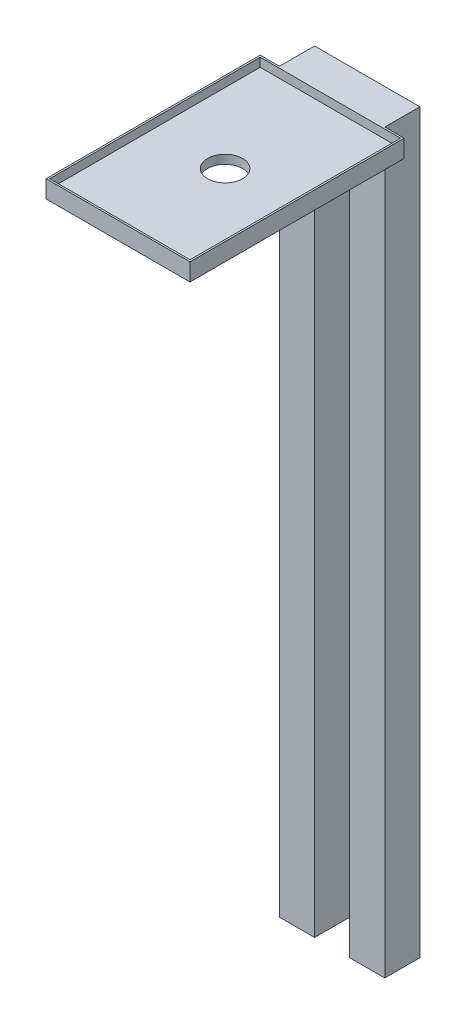
SolidWorks part; units mm, degrees
ref_plane "Front Plane" through (0, 0, 0) normal (0, 0, 1) x (1, 0, 0)
ref_plane "Top Plane" through (0, 0, 0) normal (0, 1, 0) x (1, 0, 0)
ref_plane "Right Plane" through (0, 0, 0) normal (1, 0, 0) x (0, 0, -1)
sketch "Sketch1" plane through (0, 0, 0) normal (0, 1, 0) x (1, 0, 0)
  line L1 (-20, 30) -> (20, 30)
  line L2 (-20, 30) -> (-20, -30)
  line L3 (-20, -30) -> (20, -30)
  line L4 (20, 30) -> (20, -30)
  line L5 (-20, 30) -> (20, -30) construction
  line L6 (-20, -30) -> (20, 30) construction
  circle A0 centre (0, 0) radius 5
  point P0 (0, 0)
  dimension "D1" = 10
  dimension "D2" = 60
  dimension "D3" = 40
extrude "Boss-Extrude1" add sketch "Sketch1" along normal blind 2.5
sketch "Sketch2" plane through (0, 0, 0) normal (0, -1, 0) x (1, 0, 0)
  line L0 (20.5, -30.5) -> (20.5, 30.5)
  line L1 (20.5, 30.5) -> (-20.5, 30.5)
  line L2 (-20.5, 30.5) -> (-20.5, -30.5)
  line L3 (-20.5, -30.5) -> (20.5, -30.5)
  line L4 (20, -30) -> (20, 30)
  line L5 (20, 30) -> (-20, 30)
  line L6 (-20, 30) -> (-20, -30)
  line L7 (-20, -30) -> (20, -30)
  line L8 (20, -30) -> (20, 30)
  line L9 (20, 30) -> (-20, 30)
  line L10 (-20, 30) -> (-20, -30)
  line L11 (-20, -30) -> (20, -30)
  dimension "D1" = 0
  dimension "D2" = 0.5
extrude "Boss-Extrude2" add sketch "Sketch2" against normal blind 5
sketch "Sketch3" plane through (0, 0, -30.5) normal (0, 0, -1) x (-1, 0, 0)
  line L1 (-15, 5) -> (15, 5)
  line L2 (-15, 5) -> (-15, -5)
  line L3 (-15, -5) -> (15, -5)
  line L4 (15, 5) -> (15, -5)
  line L5 (-15, 5) -> (15, -5) construction
  line L6 (-15, -5) -> (15, 5) construction
  point P0 (0, 0)
  dimension "D1" = 30
  dimension "D2" = 10
extrude "Boss-Extrude3" add sketch "Sketch3" along normal blind 10
sketch "Sketch4" plane through (0, -5, 0) normal (0, -1, 0) x (1, 0, 0)
  line L0 (15, -40.5) -> (-15, -40.5) construction
  line L1 (-15, -30.5) -> (-5, -30.5)
  line L2 (-15, -30.5) -> (-15, -40.5)
  line L3 (-15, -40.5) -> (-5, -40.5)
  line L4 (-5, -30.5) -> (-5, -40.5)
  line L5 (15, -40.5) -> (15, -30.5) construction
  line L6 (15, -30.5) -> (5, -30.5)
  line L7 (15, -30.5) -> (15, -40.5)
  line L8 (15, -40.5) -> (5, -40.5)
  line L9 (5, -30.5) -> (5, -40.5)
extrude "Boss-Extrude4" add sketch "Sketch4" along normal blind 200
